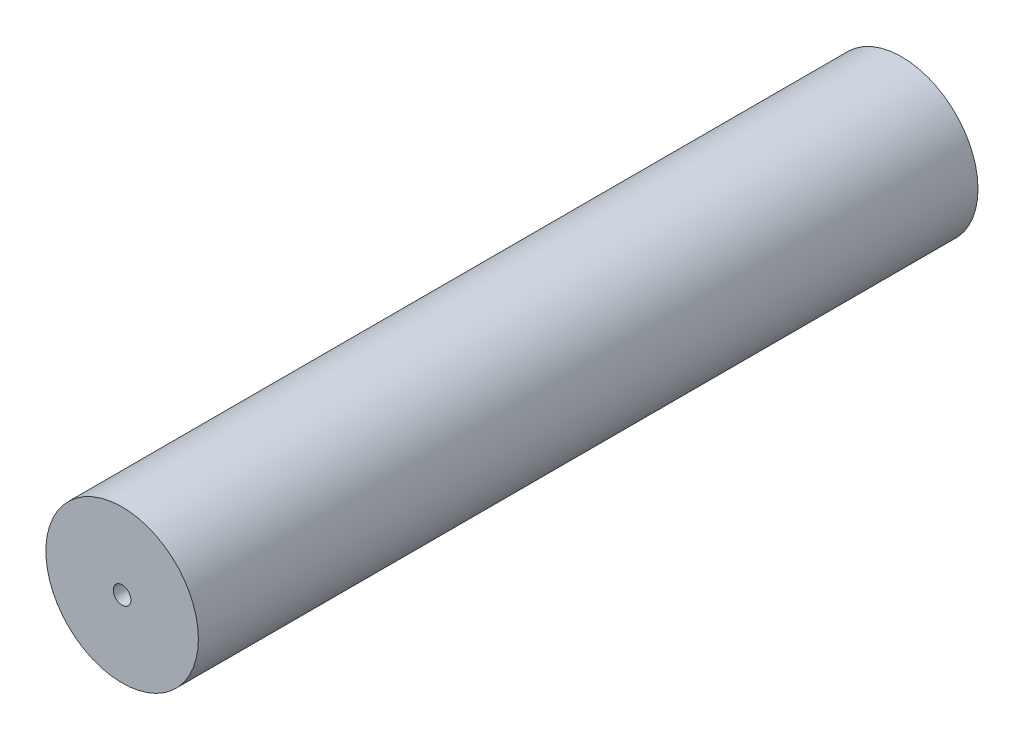
SolidWorks part; units mm, degrees
ref_plane "Front Plane" through (0, 0, 0) normal (0, 0, 1) x (1, 0, 0)
ref_plane "Top Plane" through (0, 0, 0) normal (0, 1, 0) x (1, 0, 0)
ref_plane "Right Plane" through (0, 0, 0) normal (1, 0, 0) x (0, 0, -1)
sketch "Sketch2" plane through (0, 0, 0) normal (0, 0, 1) x (1, 0, 0)
  circle A0 centre (0, 0) radius 3.302
  circle A1 centre (0, 0) radius 28.575
  dimension "D1" = 6.604
  dimension "D2" = 57.15
extrude "Boss-Extrude1" add sketch "Sketch2" along normal blind 292.1
